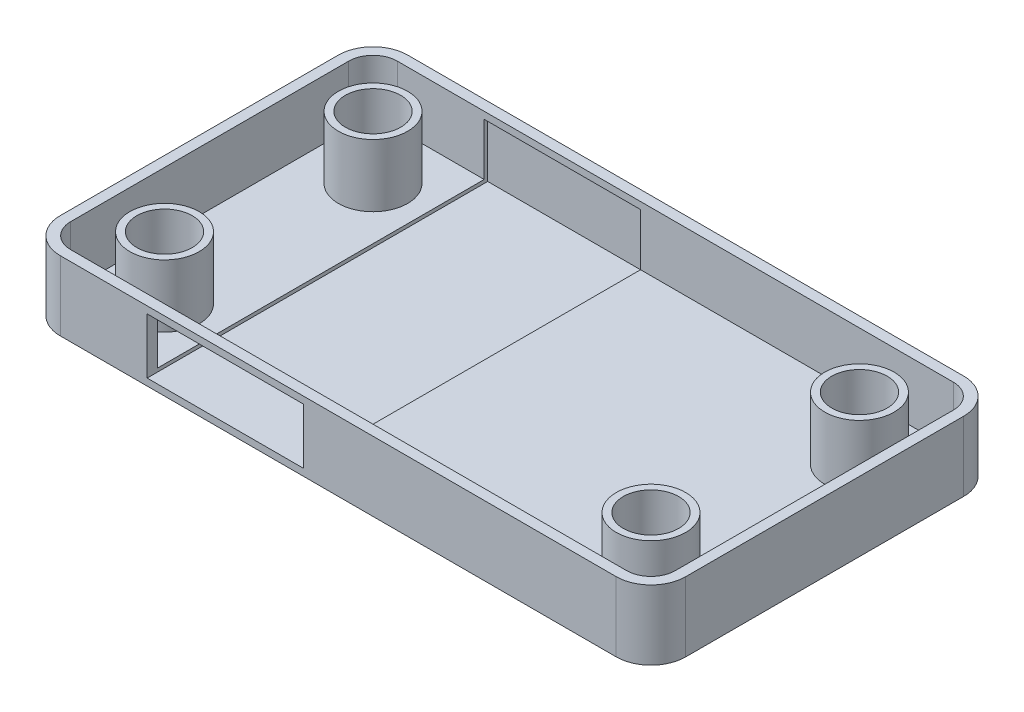
SolidWorks part; units mm, degrees
ref_plane "Front Plane" through (0, 0, 0) normal (0, 0, 1) x (1, 0, 0)
ref_plane "Top Plane" through (0, 0, 0) normal (0, 1, 0) x (1, 0, 0)
ref_plane "Right Plane" through (0, 0, 0) normal (1, 0, 0) x (0, 0, -1)
sketch "Sketch1" plane through (0, 0, 0) normal (0, 1, 0) x (1, 0, 0)
  line L1 (-80, -50) -> (80, -50)
  line L2 (-90, -40) -> (-90, 40)
  line L3 (-80, 50) -> (80, 50)
  line L4 (90, -40) -> (90, 40)
  line L5 (-90, -50) -> (90, 50) construction
  line L6 (-90, 50) -> (90, -50) construction
  arc A0 (-80, -50) -> (-90, -40) centre (-80, -40) cw
  arc A1 (-90, 40) -> (-80, 50) centre (-80, 40) cw
  arc A2 (80, -50) -> (90, -40) centre (80, -40) ccw
  arc A3 (80, 50) -> (90, 40) centre (80, 40) cw
  point P0 (0, 0)
  dimension "D3" = 10
  dimension "D1" = 180
  dimension "D2" = 100
extrude "Boss-Extrude1" add sketch "Sketch1" along normal blind 20 contours L3 A3 L4 A2 L1 A0 L2 A1
shell "Shell1" thickness 3
sketch "Sketch3" plane through (0, 3, 0) normal (0, 1, 0) x (1, 0, 0)
  line L0 (-80, 50) -> (80, 50) construction
  line L2 (-90, -40) -> (-90, 40) construction
  line L3 (-90, 0) -> (90, 0) construction
  line L4 (90, -40) -> (90, 40) construction
  line L5 (0, 47) -> (0, -50) construction
  line L6 (-80, 47) -> (80, 47) construction
  line L7 (-80, -50) -> (80, -50) construction
  circle A0 centre (-70, 30) radius 9.9729
  circle A1 centre (-70, 30) radius 7.9729
  circle A2 centre (70, 30) radius 7.9729
  circle A3 centre (70, 30) radius 9.9729
  circle A4 centre (70, -30) radius 7.9729
  circle A5 centre (70, -30) radius 9.9729
  circle A6 centre (-70, -30) radius 7.9729
  circle A7 centre (-70, -30) radius 9.9729
  dimension "D1" = 20
  dimension "D2" = 20
  dimension "D3" = 2
extrude "Boss-Extrude2" add sketch "Sketch3" along normal blind 18
sketch "Sketch4" plane through (0, 0, 50) normal (0, 0, 1) x (1, 0, 0)
  line L0 (-80, 20) -> (80, 20) construction
  line L1 (-55, 18) -> (-10, 18)
  line L2 (-55, 18) -> (-55, 2)
  line L3 (-55, 2) -> (-10, 2)
  line L4 (-10, 18) -> (-10, 2)
  line L5 (-80, 0) -> (80, 0) construction
  line L6 (-90, 20) -> (-90, 0) construction
  line L7 (90, 20) -> (90, 0) construction
  dimension "D1" = 2
  dimension "D2" = 2
  dimension "D3" = 35
  dimension "D4" = 100
extrude "Cut-Extrude2" cut sketch "Sketch4" against normal blind 98
